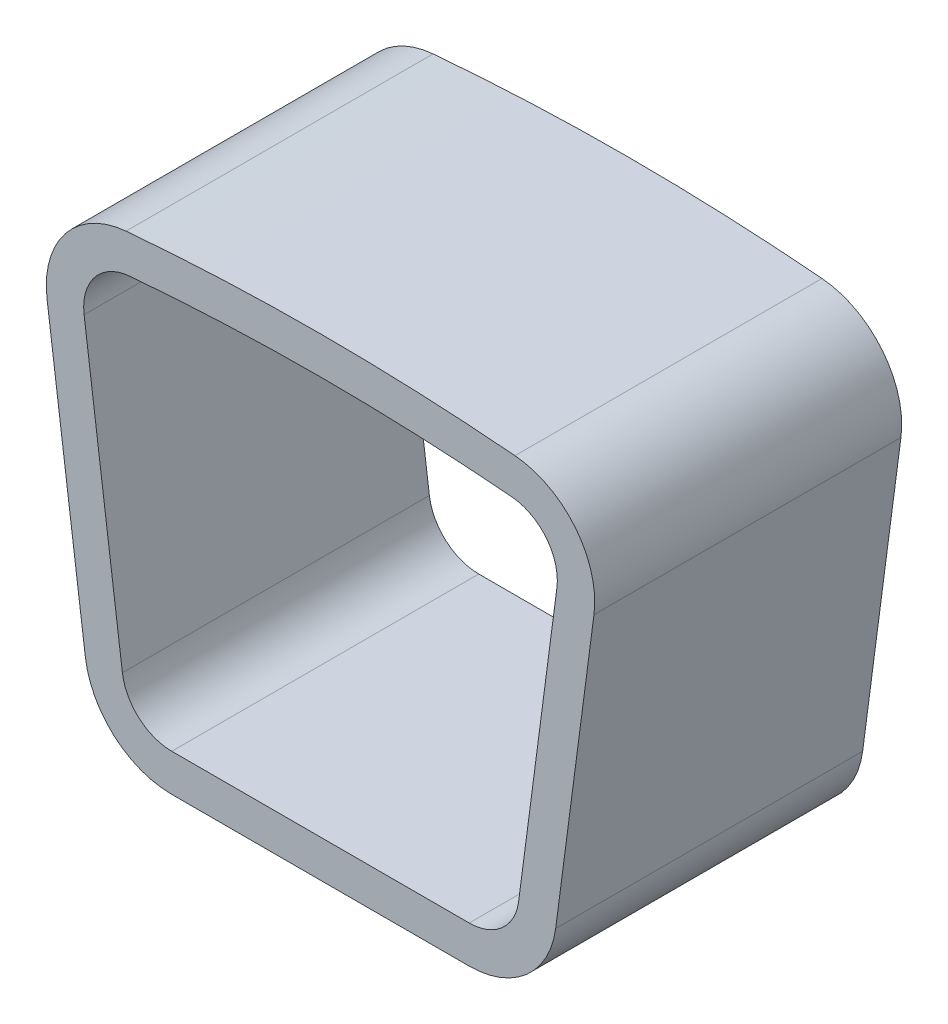
SolidWorks part; units mm, degrees
material "Copper"
ref_plane "Front Plane" through (0, 0, 0) normal (0, 0, 1) x (1, 0, 0)
ref_plane "Top Plane" through (0, 0, 0) normal (0, 1, 0) x (1, 0, 0)
ref_plane "Right Plane" through (0, 0, 0) normal (1, 0, 0) x (0, 0, -1)
sketch "Sketch1" plane through (0, 0, 0) normal (0, 0, 1) x (1, 0, 0)
  line L1 (9.4411, 75.5432) -> (10.9787, 87.2222)
  line L2 (-10.9787, 87.2222) -> (-9.4411, 75.5432)
  line L3 (-5.9711, 72.5) -> (5.9711, 72.5)
  line L4 (-9.4915, 87.418) -> (-7.954, 75.7389)
  line L5 (-5.9711, 74) -> (5.9711, 74)
  line L6 (7.954, 75.7389) -> (9.4915, 87.418)
  line L7 (-9.4915, 87.418) -> (-7.954, 75.7389)
  line L8 (-5.9711, 74) -> (5.9711, 74)
  line L9 (7.954, 75.7389) -> (9.4915, 87.418)
  arc A0 (10.9787, 87.2222) -> (7.8073, 91.1663) centre (7.5087, 87.6791) ccw
  arc A1 (7.8073, 91.1663) -> (-7.8073, 91.1663) centre (0, 0) ccw
  arc A2 (-7.8073, 91.1663) -> (-10.9787, 87.2222) centre (-7.5087, 87.6791) ccw
  arc A3 (-9.4411, 75.5432) -> (-5.9711, 72.5) centre (-5.9711, 76) ccw
  arc A4 (5.9711, 72.5) -> (9.4411, 75.5432) centre (5.9711, 76) ccw
  arc A5 (7.6793, 89.6718) -> (-7.6793, 89.6718) centre (0, 0) ccw
  arc A6 (-7.6793, 89.6718) -> (-9.4915, 87.418) centre (-7.5087, 87.6791) ccw
  arc A7 (-7.954, 75.7389) -> (-5.9711, 74) centre (-5.9711, 76) ccw
  arc A8 (5.9711, 74) -> (7.954, 75.7389) centre (5.9711, 76) ccw
  arc A9 (9.4915, 87.418) -> (7.6793, 89.6718) centre (7.5087, 87.6791) ccw
  arc A10 (7.6793, 89.6718) -> (-7.6793, 89.6718) centre (0, 0) ccw
  arc A11 (-7.6793, 89.6718) -> (-9.4915, 87.418) centre (-7.5087, 87.6791) ccw
  arc A12 (-7.954, 75.7389) -> (-5.9711, 74) centre (-5.9711, 76) ccw
  arc A13 (5.9711, 74) -> (7.954, 75.7389) centre (5.9711, 76) ccw
  arc A14 (9.4915, 87.418) -> (7.6793, 89.6718) centre (7.5087, 87.6791) ccw
  dimension "D1" = 0
  dimension "D2" = 1.5
extrude "Boss-Extrude1" add sketch "Sketch1" along normal up to surface (12.325 mm away)
